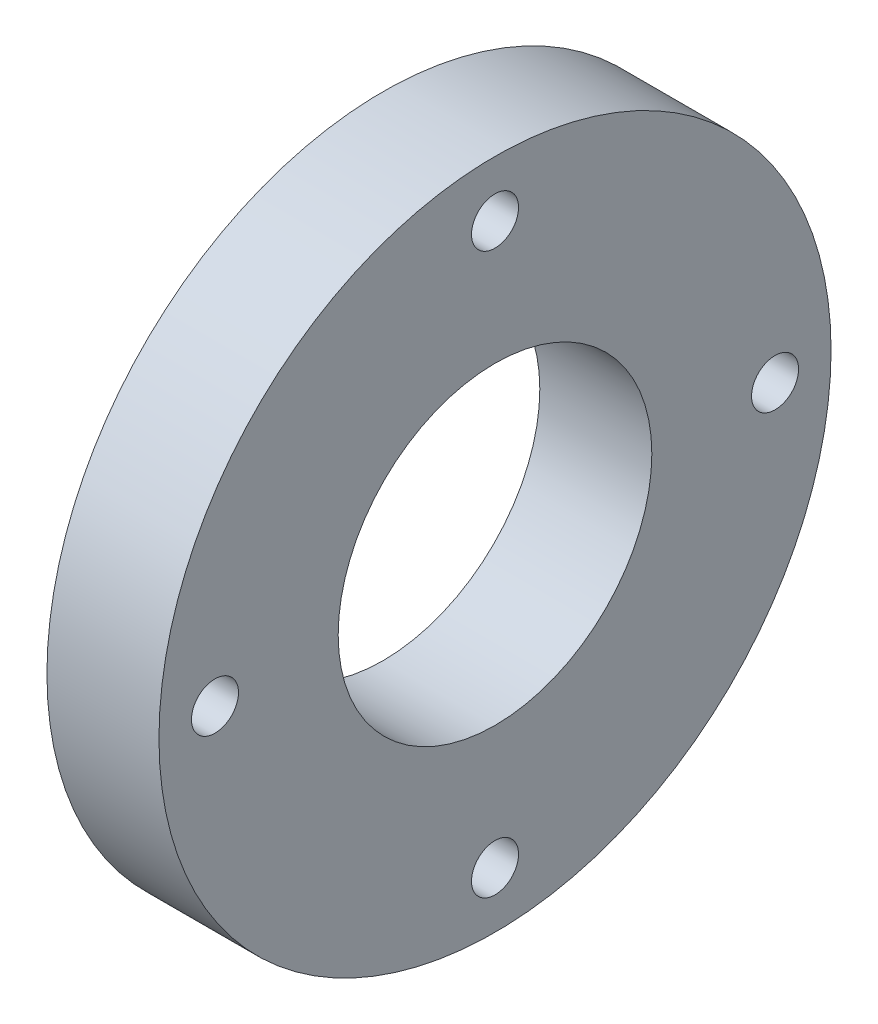
SolidWorks part; units mm, degrees
ref_plane "Front Plane" through (0, 0, 0) normal (0, 0, 1) x (1, 0, 0)
ref_plane "Top Plane" through (0, 0, 0) normal (0, 1, 0) x (1, 0, 0)
ref_plane "Right Plane" through (0, 0, 0) normal (1, 0, 0) x (0, 0, -1)
sketch "Sketch1" plane through (0, 0, 0) normal (0, 0, 1) x (1, 0, 0)
  line L0 (21, 15) -> (21, 0)
  line L1 (21, 0) -> (26, 0)
  line L2 (26, 0) -> (26, 15)
  line L3 (26, 15) -> (21, 15)
  line L4 (21, 0) -> (26, 0) construction
revolve "Revolve1" add sketch "Sketch1" angle 360 about L4
hole_wizard "Ø14.0 (14) Diameter Hole1" positions "Sketch3" profile "Sketch2" hole size "Ø14.0" standard "ANSI Metric"
sketch "Sketch3" plane through (21, 0, 0) normal (-1, 0, 0) x (0, 0, 1)
  point P0 (0, 0)
sketch "Sketch2" plane through (21, 0, 0) normal (0, 1, 0) x (0, 0, 1)
  line L0 (0, 0) -> (0, 5)
  line L1 (0, 5) -> (7, 5)
  line L2 (7, 5) -> (7, 0)
  line L5 (7, 0) -> (0, 0)
  line L11 (0, -6.35) -> (0, 107.95) construction
  dimension "Thru Hole Dia." = 14
  dimension "Thru Hole Depth" = 5
hole_wizard "Ø2.1 (2.1) Diameter Hole1" positions "Sketch5" profile "Sketch4" hole size "Ø2.1" standard "ANSI Metric"
sketch "Sketch5" plane through (26, 0, 0) normal (1, 0, 0) x (0, 0, -1)
  point P0 (-12.5, 0)
  point P1 (12.5, 0)
  point P2 (0, -12.5)
  point P3 (0, 12.5)
sketch "Sketch4" plane through (26, 0, 12.5) normal (0, 1, 0) x (0, 0, -1)
  line L0 (0, 0) -> (0, 2.5)
  line L1 (0, 2.5) -> (1.05, 2.5)
  line L2 (1.05, 2.5) -> (1.05, 0)
  line L5 (1.05, 0) -> (0, 0)
  line L10 (0, 2.5) -> (-1.05, 2.5) construction
  line L11 (0, -6.35) -> (0, 107.95) construction
  dimension "Hole Dia." = 2.1
  dimension "Hole Depth" = 2.5
  dimension "Drill Angle" = 180
